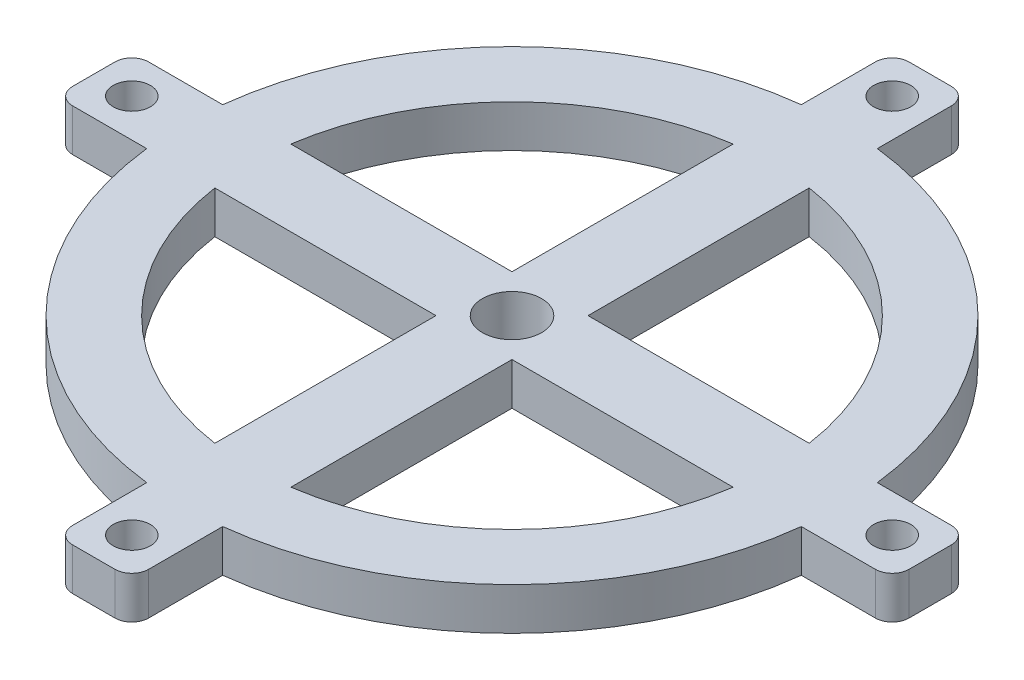
SolidWorks part; units mm, degrees
ref_plane "Alzado" through (0, 0, 0) normal (0, 0, 1) x (1, 0, 0)
ref_plane "Planta" through (0, 0, 0) normal (0, 1, 0) x (1, 0, 0)
ref_plane "Vista lateral" through (0, 0, 0) normal (1, 0, 0) x (0, 0, -1)
sketch "Croquis1" plane through (0, 0, 0) normal (0, 1, 0) x (1, 0, 0)
  line L0 (1.25, -24.75) -> (-1.25, -24.75)
  line L1 (23.75, 2.25) -> (-23.75, 2.25)
  line L2 (24.75, 1.25) -> (24.75, -1.25)
  line L3 (23.75, -2.25) -> (-23.75, -2.25)
  line L4 (-24.75, 1.25) -> (-24.75, -1.25)
  line L5 (24.75, 2.25) -> (-24.75, -2.25) construction
  line L6 (24.75, -2.25) -> (-24.75, 2.25) construction
  line L7 (2.25, -23.75) -> (2.25, 23.75)
  line L8 (1.25, 24.75) -> (-1.25, 24.75)
  line L9 (-2.25, -23.75) -> (-2.25, 23.75)
  circle A0 centre (0, 0) radius 15.5
  circle A1 centre (0, 0) radius 19.5
  arc A2 (23.75, 2.25) -> (24.75, 1.25) centre (23.75, 1.25) cw
  arc A3 (24.75, -1.25) -> (23.75, -2.25) centre (23.75, -1.25) cw
  arc A4 (-23.75, -2.25) -> (-24.75, -1.25) centre (-23.75, -1.25) cw
  arc A5 (-23.75, 2.25) -> (-24.75, 1.25) centre (-23.75, 1.25) ccw
  arc A6 (-1.25, -24.75) -> (-2.25, -23.75) centre (-1.25, -23.75) cw
  arc A7 (2.25, -23.75) -> (1.25, -24.75) centre (1.25, -23.75) cw
  arc A8 (2.25, 23.75) -> (1.25, 24.75) centre (1.25, 23.75) ccw
  arc A9 (-2.25, 23.75) -> (-1.25, 24.75) centre (-1.25, 23.75) cw
  point P35 (0, 0)
  dimension "D1" = 31
  dimension "D2" = 39
  dimension "D5" = 1
  dimension "D3" = 49.5
  dimension "D4" = 4.5
  dimension "D6" = 2
extrude "Saliente-Extruir1" add sketch "Croquis1" along normal blind 2.5 contours L3 A1 L9 A0 | L1 A5 L4 A4 L3 A1 | L1 A1 L3 A0 | A9 L9 A1 L7 A8 L8 | L9 A1 L1 A0 | L7 A1 L9 A0 | L1 A1 L7 A0 | L3 A1 L1 A0 | A3 L2 A2 L1 A1 L3 | A7 L7 A1 L9 A6 L0 | L9 A1 L7 A0 | L7 A1 L3 A0 | L9 A0 L7 L3 | L1 A0 L3 L9 | L7 A0 L9 L1 | L9 L3 L7 L1 | L3 A0 L1 L7
sketch "Croquis2" plane through (0, 2.5, 0) normal (0, 1, 0) x (1, 0, 0)
  line L0 (-24.75, 0) -> (24.75, 0) construction
  line L1 (-24.75, 1.25) -> (-24.75, -1.25) construction
  line L2 (24.75, 1.25) -> (24.75, -1.25) construction
  circle A0 centre (0, 0) radius 1.75
  circle A1 centre (0, 0) radius 22.5 construction
  circle A2 centre (-22.5, 0) radius 1.1
  circle A3 centre (0, 22.5) radius 1.1
  circle A4 centre (22.5, 0) radius 1.1
  circle A5 centre (0, -22.5) radius 1.1
  point P21 (0, 0)
  dimension "D1" = 3.5
  dimension "D2" = 45
  dimension "D3" = 2.2
  dimension "D4" = 4
extrude "Cortar-Extruir1" cut sketch "Croquis2" against normal blind 2.5
